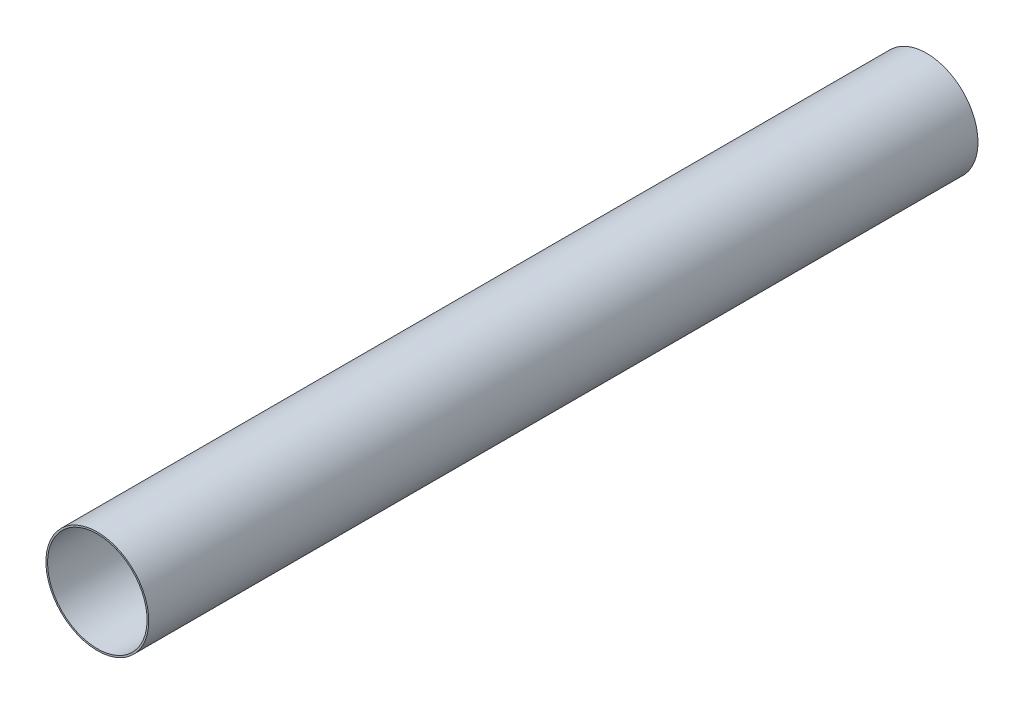
SolidWorks part; units mm, degrees
ref_plane "Front Plane" through (0, 0, 0) normal (1, 0, 0) x (0, 1, 0)
ref_plane "Top Plane" through (0, 0, 0) normal (0, 0, 1) x (0, 1, 0)
ref_plane "Right Plane" through (0, 0, 0) normal (0, 1, 0) x (-1, 0, 0)
sketch "Sketch1" plane through (0, 0, 0) normal (0, 0, 1) x (0, 1, 0)
  circle A0 centre (0, 0) radius 31
  dimension "D1" = 62
extrude "Extrude-Thin1" add sketch "Sketch1" along normal blind 500 thin thin type one direction reverse wall 1
